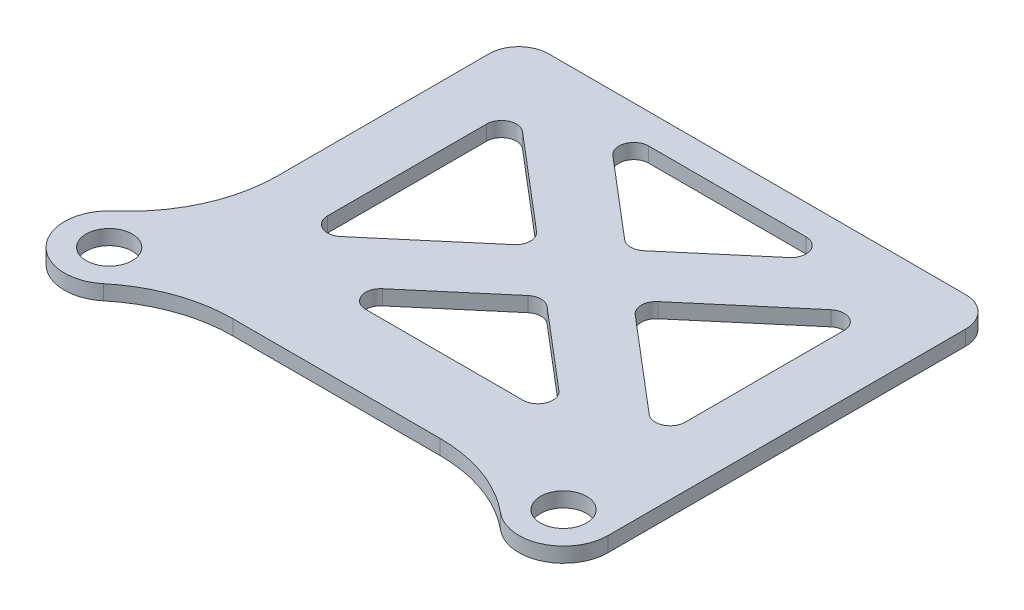
SolidWorks part; units mm, degrees
ref_plane "Front Plane" through (0, 0, 0) normal (0, 0, 1) x (1, 0, 0)
ref_plane "Top Plane" through (0, 0, 0) normal (0, 1, 0) x (1, 0, 0)
ref_plane "Right Plane" through (0, 0, 0) normal (1, 0, 0) x (0, 0, -1)
sketch "Sketch2" plane through (0, 0, 0) normal (0, 1, 0) x (1, 0, 0)
  line L0 (-15.25, 0) -> (15.25, 0) construction
  line L1 (-15.25, 0) -> (15.25, 0) construction
  line L2 (-15.25, 3) -> (15.25, 3)
  line L3 (-15.25, -3) -> (15.25, -3)
  line L4 (18.25, 0) -> (18.25, 26)
  line L5 (18.25, 26) -> (-13.75, 26)
  line L6 (-13.75, 26) -> (-13.75, 3)
  line L7 (-12.25, 0) -> (12.25, 0)
  line L8 (-9.75, 22) -> (-9.75, 7)
  line L9 (-9.75, 7) -> (-0.9265, 14.5)
  line L10 (-0.9265, 14.5) -> (-9.75, 22)
  line L11 (14.25, 22) -> (5.4265, 14.5)
  line L12 (5.4265, 14.5) -> (14.25, 7)
  line L13 (14.25, 7) -> (14.25, 22)
  line L14 (10.25, 5) -> (-5.75, 5)
  line L15 (-5.75, 5) -> (2.25, 11.8)
  line L16 (2.25, 11.8) -> (10.25, 5)
  line L17 (10.25, 24) -> (-5.75, 24)
  line L18 (-5.75, 24) -> (2.25, 17.2)
  line L19 (2.25, 17.2) -> (10.25, 24)
  circle A0 centre (-15.25, 0) radius 1.55
  circle A1 centre (15.25, 0) radius 1.55
  arc A2 (-15.25, 3) -> (-15.25, -3) centre (-15.25, 0) ccw
  arc A3 (15.25, -3) -> (15.25, 3) centre (15.25, 0) ccw
  arc A4 (-15.25, -3) -> (-12.25, 0) centre (-15.25, 0) ccw
  arc A5 (15.25, -3) -> (12.25, 0) centre (15.25, 0) cw
  point P5 (0, 0)
  point P31 (-3.0512, 15.2748)
  point P33 (15, 23)
  point P34 (-5.664, 6)
  point P35 (8.8996, 6)
  point P36 (0.995, 16.7635)
  point P37 (6.608, 14.6624)
  point P38 (-2.3408, 14.5182)
  point P39 (2.2113, 17.1829)
  point P40 (1.9893, 17.1829)
  point P41 (5.1765, 14.5)
  dimension "D2" = 3.1
  dimension "D3" = 3.1
  dimension "D5" = 3
  dimension "D1" = 30.5
  dimension "D4" = 32
  dimension "D6" = 23
  dimension "D8" = 4
  dimension "D9" = 4
  dimension "D10" = 2
  dimension "D11" = 2
  dimension "D12" = 4
  dimension "D13" = 4
  dimension "D14" = 4
  dimension "D15" = 4
  dimension "D16" = 8
  dimension "D17" = 8
  dimension "D18" = 8
  dimension "D19" = 8
extrude "Boss-Extrude1" add sketch "Sketch2" along normal blind 1 contours A3 L4 L5 L6 L2 L19 L18 L17 L13 L12 L11 L10 L9 L8 L15 L16 L14 | A5 A3 L2 A2 A4 L7 A1 A0
fillet "Fillet1" radius 10 3 edges at (-13.75, 0.5, -3) (12.25, 0.5, 0) (-12.25, 0.5, 0)
fillet "Fillet2" radius 2 2 edges at (18.25, 0.5, -26) (-13.75, 0.5, -26)
fillet "Fillet3" radius 1 12 edges at (10.25, 0.5, -24) (14.25, 0.5, -22) (14.25, 0.5, -7) (10.25, 0.5, -5) (2.25, 0.5, -11.8) (5.4265, 0.5, -14.5) (2.25, 0.5, -17.2) (-0.9265, 0.5, -14.5) (-5.75, 0.5, -5) (-9.75, 0.5, -7) (-5.75, 0.5, -24) (-9.75, 0.5, -22)
